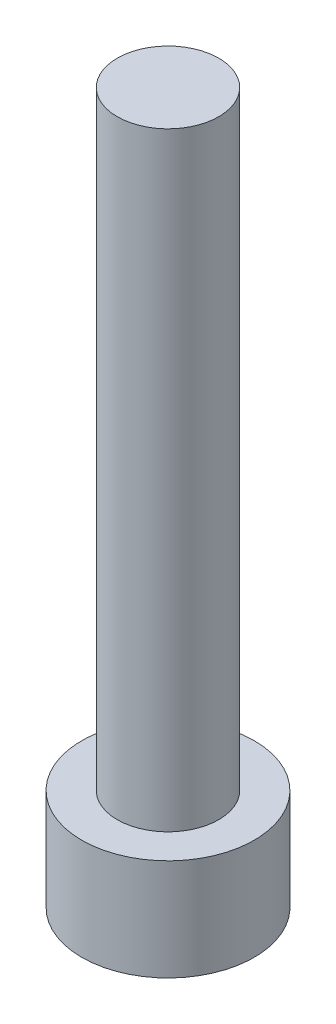
SolidWorks part; units mm, degrees
ref_plane "前视基准面" through (0, 0, 0) normal (0, 0, 1) x (1, 0, 0)
ref_plane "上视基准面" through (0, 0, 0) normal (0, 1, 0) x (1, 0, 0)
ref_plane "右视基准面" through (0, 0, 0) normal (1, 0, 0) x (0, 0, -1)
other "Configuration Table"
sketch "草图1" plane through (0, 0, 0) normal (0, 1, 0) x (1, 0, 0)
  circle A0 centre (0, 0) radius 4.25
  dimension "D1" = 8.5
extrude "凸台-拉伸1" add sketch "草图1" along normal blind 5
sketch "草图2" plane through (0, 0, 0) normal (0, 1, 0) x (1, 0, 0)
  circle A0 centre (0, 0) radius 2.5
  dimension "D1" = 5
extrude "凸台-拉伸2" add sketch "草图2" along normal blind 30 from surface at 5 starting at face at (0, 5, 4.25)
sketch "草图4" plane through (0, 0, 0) normal (0, 1, 0) x (1, 0, 0)
  line L1 (2.3094, 0) -> (1.1547, 2)
  line L2 (1.1547, 2) -> (-1.1547, 2)
  line L3 (-1.1547, 2) -> (-2.3094, 0)
  line L4 (-2.3094, 0) -> (-1.1547, -2)
  line L5 (-1.1547, -2) -> (1.1547, -2)
  line L6 (1.1547, -2) -> (2.3094, 0)
  circle A0 centre (0, 0) radius 2 construction
  dimension "D1" = 4
extrude "切除-拉伸1" cut sketch "草图4" along normal blind 2.5
